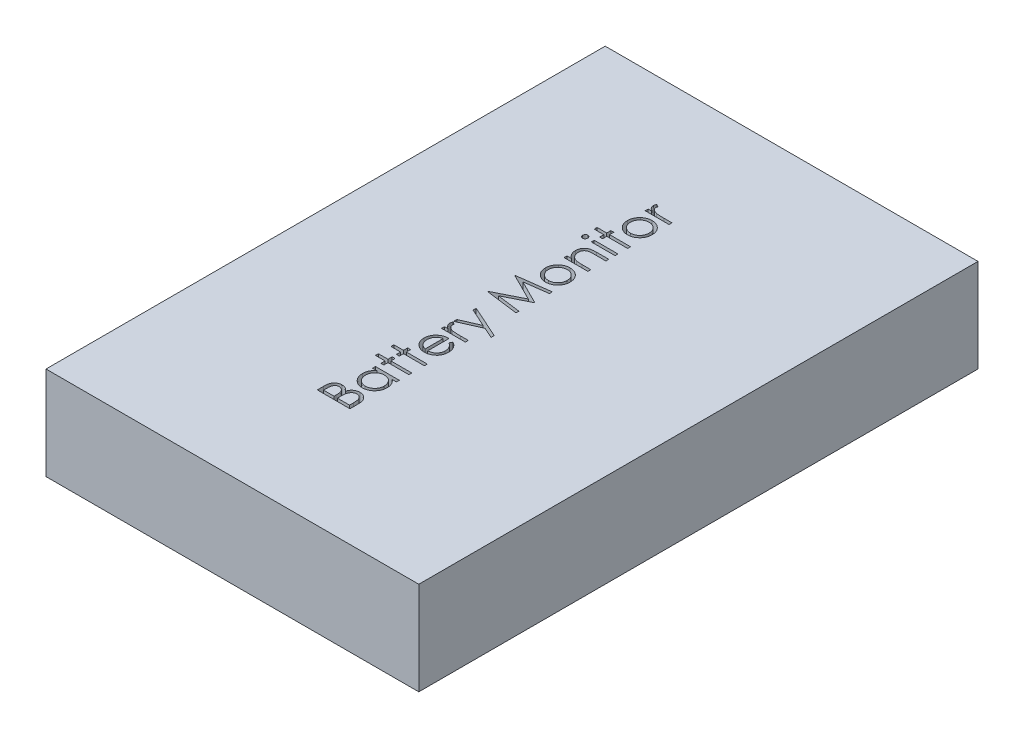
SolidWorks part; units mm, degrees
ref_plane "Front Plane" through (0, 0, 0) normal (0, 0, 1) x (1, 0, 0)
ref_plane "Top Plane" through (0, 0, 0) normal (0, 1, 0) x (1, 0, 0)
ref_plane "Right Plane" through (0, 0, 0) normal (1, 0, 0) x (0, 0, -1)
sketch "Sketch1" plane through (0, 0, 0) normal (0, 1, 0) x (1, 0, 0)
  line L1 (-20, 30) -> (20, 30)
  line L2 (-20, 30) -> (-20, -30)
  line L3 (-20, -30) -> (20, -30)
  line L4 (20, 30) -> (20, -30)
  line L5 (-20, 30) -> (20, -30) construction
  line L6 (-20, -30) -> (20, 30) construction
  point P0 (0, 0)
  dimension "D1" = 40
  dimension "D2" = 60
extrude "Boss-Extrude1" add sketch "Sketch1" along normal blind 10
sketch "Sketch2" plane through (0, 10, 0) normal (0, 1, 0) x (1, 0, 0)
  line L0 (0, -30) -> (0, 30) construction
  line L1 (-20, -30) -> (20, -30) construction
  line L2 (20, 30) -> (-20, 30) construction
  text T0 "Battery Monitor"
extrude "Cut-Extrude1" cut sketch "Sketch2" against normal blind 2
